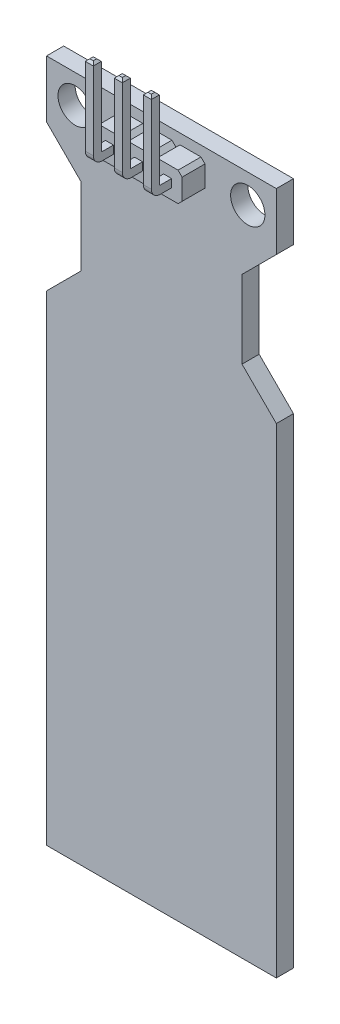
SolidWorks part; units mm, degrees
ref_plane "前视基准面" through (0, 0, 0) normal (0, 0, 1) x (1, 0, 0)
ref_plane "上视基准面" through (0, 0, 0) normal (0, 1, 0) x (1, 0, 0)
ref_plane "右视基准面" through (0, 0, 0) normal (1, 0, 0) x (0, 0, -1)
sketch "草图1" plane through (0, 0, 0) normal (0, 0, 1) x (1, 0, 0)
  line L0 (0, 29.3089) -> (0, -28.1452) construction
  line L3 (-10.05, -29.9) -> (10.05, -29.9)
  line L4 (10.05, -29.9) -> (10.05, 12.1)
  line L5 (10.05, 12.1) -> (7.05, 15.1)
  line L6 (7.05, 15.1) -> (7.05, 21.9)
  line L7 (7.05, 21.9) -> (10.05, 24.9)
  line L8 (10.05, 24.9) -> (10.05, 29.9)
  line L9 (10.05, 29.9) -> (-10.05, 29.9)
  line L12 (-10.05, -29.9) -> (-10.05, 12.1)
  line L13 (-10.05, 12.1) -> (-7.05, 15.1)
  line L14 (-7.05, 15.1) -> (-7.05, 21.9)
  line L15 (-7.05, 21.9) -> (-10.05, 24.9)
  line L16 (-10.05, 24.9) -> (-10.05, 29.9)
  line L17 (-26.233, 0) -> (46.6127, 0) construction
  circle A0 centre (7.55, 27.4) radius 1.5
  circle A1 centre (-7.55, 27.4) radius 1.5
  point P11 (0, -29.9)
  point P17 (0, 29.9)
  dimension "D7" = 3
  dimension "D1" = 135
  dimension "D2" = 59.8
  dimension "D3" = 5
  dimension "D4" = 42
  dimension "D5" = 14.1
  dimension "D6" = 20.1
  dimension "D8" = 2.5
  dimension "D9" = 2.5
extrude "凸台-拉伸1" add sketch "草图1" along normal blind 1.5
sketch "草图2" plane through (0, 0, 1.5) normal (0, 0, 1) x (1, 0, 0)
  line L0 (0, 38.6086) -> (0, 31.9627) construction
  line L1 (-3.4564, 29) -> (-3.81, 28.6464)
  line L2 (-3.81, 28.6464) -> (-3.81, 26.8136)
  line L3 (-3.81, 26.8136) -> (-3.4564, 26.46)
  line L4 (-3.4564, 26.46) -> (-1.6236, 26.46)
  line L5 (-1.6236, 26.46) -> (-1.27, 26.8136)
  line L7 (-1.27, 28.6464) -> (-1.6236, 29)
  line L8 (-1.6236, 29) -> (-3.4564, 29)
  line L9 (10.05, 29.9) -> (-10.05, 29.9) construction
  line L10 (0.9164, 29) -> (-0.9164, 29)
  line L11 (-0.9164, 29) -> (-1.27, 28.6464)
  line L13 (-1.27, 26.8136) -> (-0.9164, 26.46)
  line L14 (-0.9164, 26.46) -> (0.9164, 26.46)
  line L15 (0.9164, 26.46) -> (1.27, 26.8136)
  line L17 (1.27, 28.6464) -> (0.9164, 29)
  line L18 (3.4564, 29) -> (1.6236, 29)
  line L19 (1.6236, 29) -> (1.27, 28.6464)
  line L21 (1.27, 26.8136) -> (1.6236, 26.46)
  line L22 (1.6236, 26.46) -> (3.4564, 26.46)
  line L23 (3.4564, 26.46) -> (3.81, 26.8136)
  line L24 (3.81, 26.8136) -> (3.81, 28.6464)
  line L25 (3.81, 28.6464) -> (3.4564, 29)
  line L26 (-1.27, 28.6464) -> (-1.27, 26.8136) [skipped]
  line L27 (1.27, 28.6464) -> (1.27, 26.8136) [skipped]
  dimension "D2" = 2.54
  dimension "D3" = 0.5
  dimension "D5" = 0.9
  dimension "D6" = 135
  dimension "D7" = 3
sketch "草图3" plane through (0, 0, 1.5) normal (0, 0, 1) x (1, 0, 0)
  line L0 (-3.4564, 29) -> (-3.81, 28.6464) construction
  line L1 (-3.81, 28.6464) -> (-3.81, 26.8136) construction
  line L2 (-3.81, 26.8136) -> (-3.4564, 26.46) construction
  line L3 (-3.4564, 26.46) -> (-1.6236, 26.46) construction
  line L4 (-1.6236, 26.46) -> (-1.27, 26.8136) construction
  line L5 (-1.27, 26.8136) -> (-0.9164, 26.46) construction
  line L6 (-0.9164, 26.46) -> (0.9164, 26.46) construction
  line L7 (0.9164, 26.46) -> (1.27, 26.8136) construction
  line L8 (1.27, 26.8136) -> (1.6236, 26.46) construction
  line L9 (1.6236, 26.46) -> (3.4564, 26.46) construction
  line L10 (3.4564, 26.46) -> (3.81, 26.8136) construction
  line L11 (3.81, 26.8136) -> (3.81, 28.6464) construction
  line L12 (3.81, 28.6464) -> (3.4564, 29) construction
  line L13 (3.4564, 29) -> (1.6236, 29) construction
  line L14 (1.6236, 29) -> (1.27, 28.6464) construction
  line L15 (1.27, 28.6464) -> (0.9164, 29) construction
  line L16 (0.9164, 29) -> (-0.9164, 29) construction
  line L17 (-0.9164, 29) -> (-1.27, 28.6464) construction
  line L18 (-1.27, 28.6464) -> (-1.6236, 29) construction
  line L19 (-1.6236, 29) -> (-3.4564, 29) construction
  line L20 (-3.4564, 29) -> (-3.81, 28.6464)
  line L21 (-3.81, 28.6464) -> (-3.81, 26.8136)
  line L22 (-3.81, 26.8136) -> (-3.4564, 26.46)
  line L23 (-3.4564, 26.46) -> (-1.6236, 26.46)
  line L24 (-1.6236, 26.46) -> (-1.27, 26.8136)
  line L25 (-1.27, 26.8136) -> (-0.9164, 26.46)
  line L26 (-0.9164, 26.46) -> (0.9164, 26.46)
  line L27 (0.9164, 26.46) -> (1.27, 26.8136)
  line L28 (1.27, 26.8136) -> (1.6236, 26.46)
  line L29 (1.6236, 26.46) -> (3.4564, 26.46)
  line L30 (3.4564, 26.46) -> (3.81, 26.8136)
  line L31 (3.81, 26.8136) -> (3.81, 28.6464)
  line L32 (3.81, 28.6464) -> (3.4564, 29)
  line L33 (3.4564, 29) -> (1.6236, 29)
  line L34 (1.6236, 29) -> (1.27, 28.6464)
  line L35 (1.27, 28.6464) -> (0.9164, 29)
  line L36 (0.9164, 29) -> (-0.9164, 29)
  line L37 (-0.9164, 29) -> (-1.27, 28.6464)
  line L38 (-1.27, 28.6464) -> (-1.6236, 29)
  line L39 (-1.6236, 29) -> (-3.4564, 29)
extrude "凸台-拉伸2" add sketch "草图3" along normal blind 2
sketch "草图4" plane through (0, 0, 3.5) normal (0, 0, 1) x (1, 0, 0)
  line L0 (-4.7169, 27.73) -> (-4.0101, 27.73) construction
  line L1 (-2.89, 28.08) -> (-2.19, 28.08)
  line L2 (-2.89, 28.08) -> (-2.89, 27.38)
  line L3 (-2.89, 27.38) -> (-2.19, 27.38)
  line L4 (-2.19, 28.08) -> (-2.19, 27.38)
  line L5 (-1.6236, 29) -> (-3.4564, 29) construction
  line L6 (-3.4564, 26.46) -> (-1.6236, 26.46) construction
  line L7 (-2.54, 31.0025) -> (-2.54, 30.1491) construction
  line L8 (-0.35, 28.08) -> (-0.35, 27.38)
  line L9 (-0.35, 28.08) -> (0.35, 28.08)
  line L10 (0.35, 28.08) -> (0.35, 27.38)
  line L11 (-0.35, 27.38) -> (0.35, 27.38)
  line L12 (2.19, 28.08) -> (2.19, 27.38)
  line L13 (2.19, 28.08) -> (2.89, 28.08)
  line L14 (2.89, 28.08) -> (2.89, 27.38)
  line L15 (2.19, 27.38) -> (2.89, 27.38)
  dimension "D1" = 0.7
  dimension "D2" = 3
extrude "凸台-拉伸3" add sketch "草图4" along normal blind 1
sketch "草图5" plane through (2.89, 0, 0) normal (1, 0, 0) x (0, 0, -1)
  line L0 (-3.5, 27.38) -> (-4.5, 27.38)
  line L1 (-5.271, 28.151) -> (-5.271, 35.151)
  line L2 (-5.271, 35.151) -> (-4.571, 35.151)
  line L3 (-4.571, 35.151) -> (-4.571, 28.151)
  line L4 (-4.5, 28.08) -> (-3.5, 28.08)
  line L5 (-3.5, 28.08) -> (-3.5, 27.38)
  arc A0 (-4.5, 27.38) -> (-5.271, 28.151) centre (-4.5, 28.151) cw
  arc A1 (-4.571, 28.151) -> (-4.5, 28.08) centre (-4.5, 28.151) ccw
extrude "凸台-拉伸4" add sketch "草图5" against normal blind 0.7
pattern_linear "阵列(线性)1" count 3 spacing 2.54 along (-1, 0, 0) of "凸台-拉伸4"
chamfer "倒角1" distance 0.2 angle 45 12 edges at (2.89, 35.151, 4.921) (2.19, 35.151, 4.921) (2.54, 35.151, 4.571) (2.54, 35.151, 5.271) (0, 35.151, 5.271) (0.35, 35.151, 4.921) (-0.35, 35.151, 4.921) (0, 35.151, 4.571) (-2.19, 35.151, 4.921) (-2.89, 35.151, 4.921) (-2.54, 35.151, 4.571) (-2.54, 35.151, 5.271)
